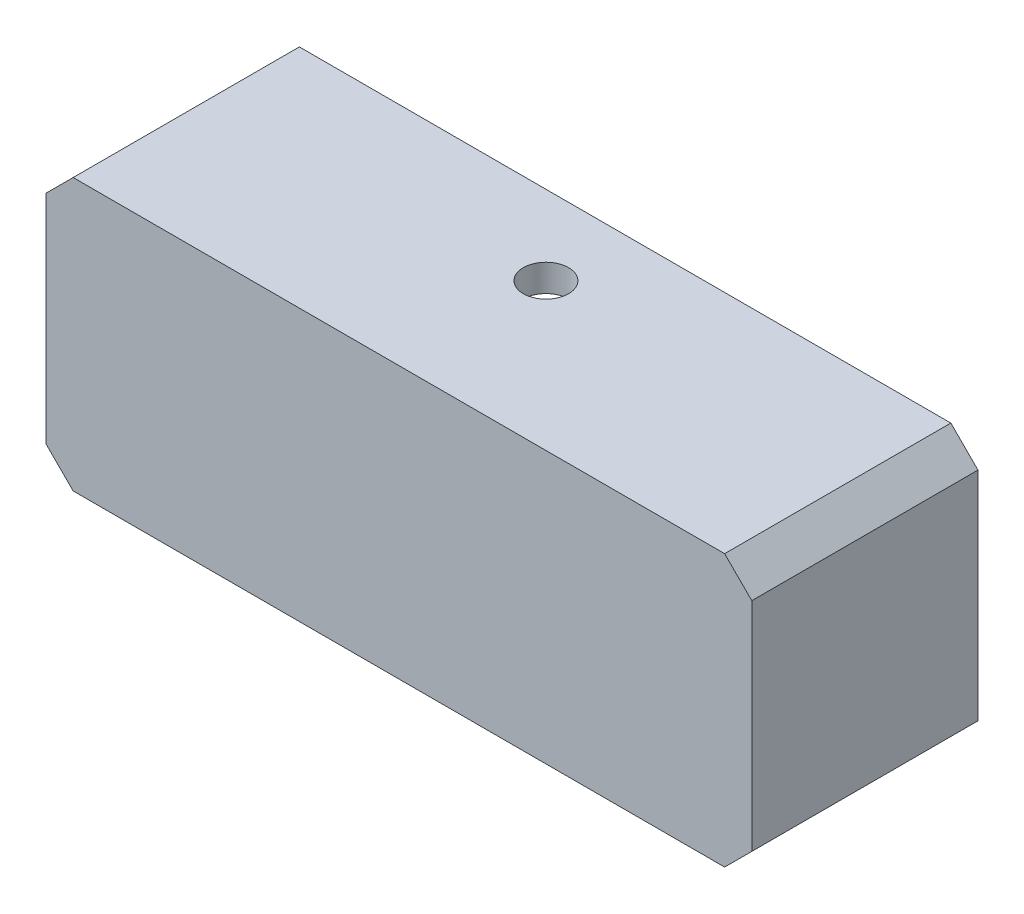
SolidWorks part; units mm, degrees
ref_plane "前视基准面" through (0, 0, 0) normal (0, 0, 1) x (1, 0, 0)
ref_plane "上视基准面" through (0, 0, 0) normal (0, 1, 0) x (1, 0, 0)
ref_plane "右视基准面" through (0, 0, 0) normal (1, 0, 0) x (0, 0, -1)
other "Configuration Table"
sketch "草图1" plane through (0, 0, 0) normal (0, 0, 1) x (1, 0, 0)
  line L1 (0, 0) -> (70, 0)
  line L2 (0, 0) -> (0, 20)
  line L3 (0, 20) -> (70, 20)
  line L4 (70, 0) -> (70, 20)
  dimension "D1" = 70
  dimension "D2" = 20
extrude "凸台-拉伸1" add sketch "草图1" along normal blind 3
sketch "草图2" plane through (0, 0, 3) normal (0, 0, 1) x (1, 0, 0)
  line L0 (70, 20) -> (0, 20) construction
  line L1 (-4, 27) -> (74, 27)
  line L2 (-4, 27) -> (-4, -3)
  line L3 (-4, -3) -> (74, -3)
  line L4 (74, 27) -> (74, -3)
  line L5 (0, 0) -> (70, 0) construction
  line L6 (70, 0) -> (70, 20) construction
  line L7 (0, 20) -> (0, 0) construction
  dimension "D1" = 7
  dimension "D2" = 3
  dimension "D3" = 4
  dimension "D4" = 4
extrude "凸台-拉伸2" add sketch "草图2" against normal blind 3
sketch "草图4" plane through (0, 0, 0) normal (0, 0, -1) x (-1, 0, 0)
  line L0 (-74, 9) -> (-74, -3)
  line L1 (-74, -3) -> (-74, 27) construction
  line L2 (-74, -3) -> (-58, -3)
  line L3 (4, -3) -> (-74, -3) construction
  line L4 (-58, -3) -> (-58, 9)
  line L5 (-58, 9) -> (-74, 9)
  line L6 (-61, 6.5) -> (-61, 0) construction
  line L8 (-60.9, 6.5) -> (-70, 6.5)
  line L9 (-60.9, 6.5) -> (-60.9, 0)
  line L10 (-60.9, 0) -> (-70, 0)
  line L11 (-70, 6.5) -> (-70, 0)
  dimension "D1" = 12
  dimension "D2" = 3
  dimension "D3" = 9.1
extrude "凸台-拉伸3" add sketch "草图4" along normal blind 22
ref_plane "基准面1" through (35, 0, 0) normal (1, 0, 0) x (0, 0, -1)
mirror "镜向1" about plane through (35, 0, 0) normal (1, 0, 0) of "凸台-拉伸3"
sketch "草图5" plane through (0, 0, 0) normal (0, 0, -1) x (-1, 0, 0)
  line L0 (-58, -3) -> (-58, 9) construction
  line L1 (-12, -3) -> (-58, -3)
  line L2 (-12, -3) -> (-12, 0)
  line L3 (-12, 0) -> (-58, 0)
  line L4 (-58, -3) -> (-58, 0)
  dimension "D1" = 3
extrude "凸台-拉伸4" add sketch "草图5" along normal blind 22
sketch "草图6" plane through (0, 0, 0) normal (0, 0, -1) x (-1, 0, 0)
  line L0 (-74, 9) -> (-74, 27) construction
  line L1 (4, 27) -> (-74, 27)
  line L2 (4, 27) -> (4, 24)
  line L3 (1, 24) -> (-71, 24)
  line L4 (-74, 27) -> (-74, 24)
  line L6 (4, 9) -> (1, 9)
  line L7 (4, 9) -> (4, 24)
  line L9 (1, 9) -> (1, 24)
  line L10 (-74, 9) -> (-71, 9)
  line L11 (-74, 9) -> (-74, 24)
  line L13 (-71, 9) -> (-71, 24)
  dimension "D1" = 3
  dimension "D2" = 3
  dimension "D3" = 3
extrude "凸台-拉伸5" add sketch "草图6" along normal blind 22
sketch "草图7" plane through (0, 0, -22) normal (0, 0, -1) x (-1, 0, 0)
  line L0 (-74, 27) -> (-74, -3) construction
  line L1 (4, 27) -> (-74, 27)
  line L2 (4, 27) -> (4, 24)
  line L3 (4, 24) -> (-74, 24)
  line L4 (-74, 27) -> (-74, 24)
chamfer "倒角1" distance 3 angle 45 4 edges at (-4, 27, -9.5) (-4, -3, -9.5) (74, -3, -9.5) (74, 27, -9.5)
sketch "草图10" plane through (0, 24, 0) normal (0, -1, 0) x (1, 0, 0)
  line L0 (71, -22) -> (-1, -22) construction
  line L1 (71, -22) -> (-1, -22) construction
  circle A2 centre (35, -13.25) radius 2.5
  point P8 (35, -22)
  dimension "D1" = 8.75
extrude "切除-拉伸1" cut sketch "草图10" against normal through all and the other way through all
sketch "草图11" plane through (0, 6.5, 0) normal (0, -1, 0) x (1, 0, 0)
  line L0 (9.1, -22) -> (0, -22) construction
  line L1 (9.1, 0) -> (0, 0) construction
  circle A0 centre (4.55, -8) radius 1.65
  point P4 (4.55, -22)
  dimension "D1" = 3.3
  dimension "D2" = 8
extrude "切除-拉伸2" cut sketch "草图11" against normal blind 10 and the other way blind 10
mirror "镜向2" about plane through (35, 0, 0) normal (1, 0, 0) of "切除-拉伸2"
